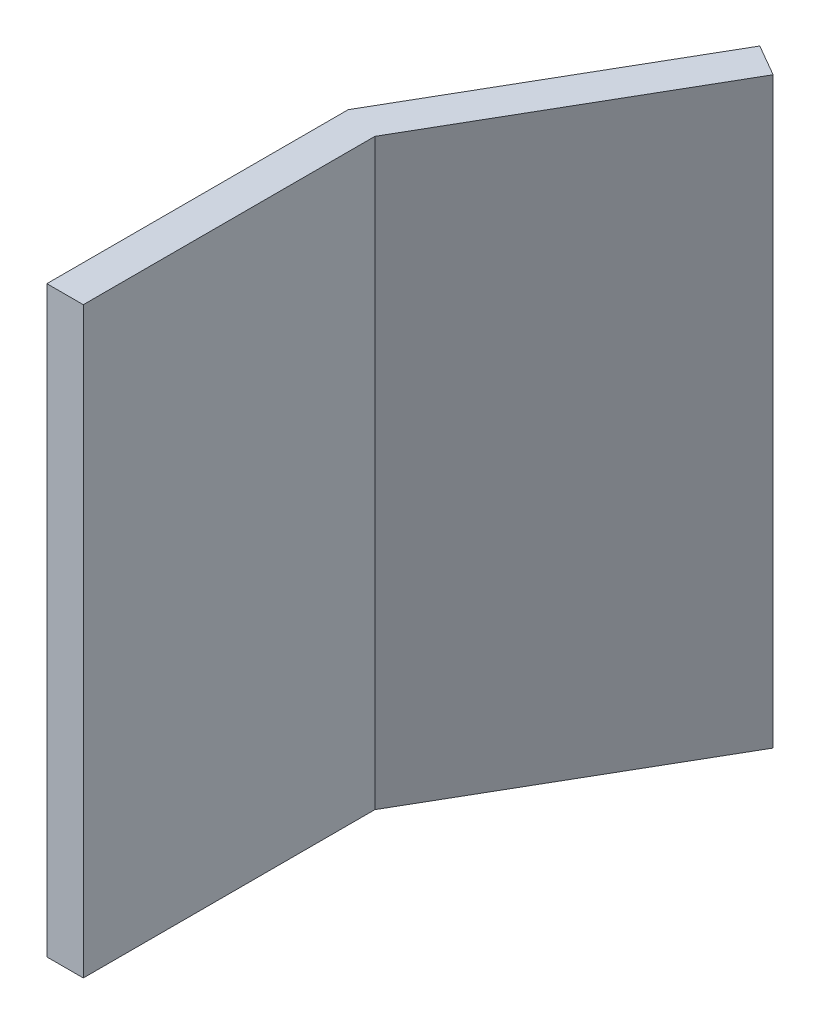
SolidWorks part; units mm, degrees
ref_plane "Front" through (0, 0, 0) normal (0, 0, 1) x (1, 0, 0)
ref_plane "Top" through (0, 0, 0) normal (0, 1, 0) x (1, 0, 0)
ref_plane "Right" through (0, 0, 0) normal (1, 0, 0) x (0, 0, -1)
sketch "Sketch1" plane through (0, 0, 0) normal (0, 1, 0) x (1, 0, 0)
  line L0 (13.1254, 22.7338) -> (15.875, 21.1463)
  line L1 (13.1254, 22.7338) -> (0, 0)
  line L2 (15.875, 21.1463) -> (2.7496, -1.5875)
  line L3 (0, 0) -> (2.7496, -1.5875)
  line L4 (0, 0) -> (3.175, 0)
  line L5 (0, 0) -> (0, -26.2507)
  line L6 (3.175, 0) -> (3.175, -26.2507)
  line L7 (0, -26.2507) -> (3.175, -26.2507)
  point P10 (3.175, -0.8507)
  dimension "D1" = 30
  dimension "D2" = 25.4
  dimension "D4" = 3.175
extrude "Boss-Extrude1" add sketch "Sketch1" along normal blind 50.8 contours L5 L7 L6 L2 L3 | L4 L6 L2 L0 L1 | L6 L4 L3 L2
